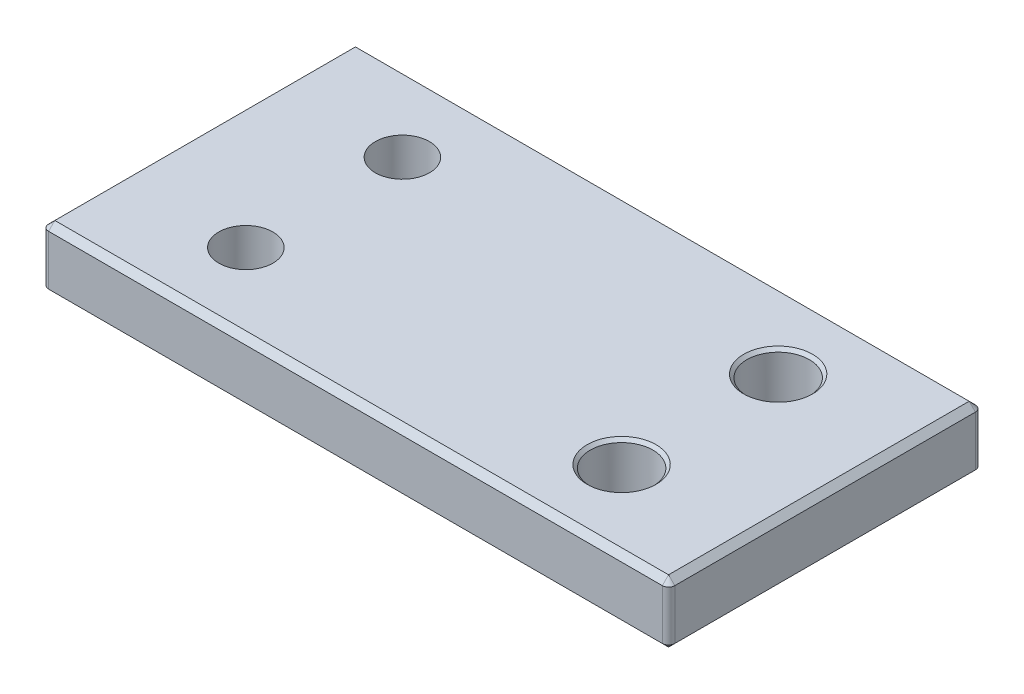
SolidWorks part; units mm, degrees
ref_plane "前基準面" through (0, 0, 0) normal (0, 0, 1) x (1, 0, 0)
ref_plane "上基準面" through (0, 0, 0) normal (0, 1, 0) x (1, 0, 0)
ref_plane "右基準面" through (0, 0, 0) normal (1, 0, 0) x (0, 0, -1)
ref_plane "平面1"
sketch "草圖1" plane through (0, 0, 0) normal (0, 1, 0) x (-1, 0, 0)
  line L0 (50, -25) -> (-50, -25)
  line L1 (-50, -25) -> (-50, 25)
  line L2 (-50, 25) -> (50, 25)
  line L3 (50, 25) -> (50, -25)
  dimension "D1" = 100
  dimension "D2" = 50
extrude "擠出1" add sketch "草圖1" along normal blind 10
sketch "草圖2" plane through (0, 10, 0) normal (0, 1, 0) x (-1, 0, 0)
  line L0 (50, -25) -> (50, 25) construction
  circle A0 centre (-30, -12.5) radius 5
  circle A1 centre (-30, 12.5) radius 5
  dimension "D1" = 10
  dimension "D2" = 10
  dimension "D3" = 25
  dimension "D4" = 32.5
  dimension "D5" = 80
extrude "擠出2" cut sketch "草圖2" against normal blind 10
hole_wizard "孔1" positions "草圖4" profile "草圖3" legacy
sketch "草圖4" plane through (0, 10, 0) normal (0, 1, 0) x (1, 0, 0)
  point P1 (-30, -12.5)
  point P2 (-30, 12.5)
sketch "草圖3" plane through (-30, 10, 12.5) normal (1, 0, 0) x (0, 0, 1)
  line L0 (0, 0) -> (0, 28.7978)
  line L1 (0, 28.7978) -> (4.3235, 26.2)
  line L2 (4.3235, 26.2) -> (4.3235, 0)
  line L4 (4.3235, 0) -> (0, 0)
  line L6 (0, 28.7978) -> (-4.3235, 26.2) construction
  line L7 (0, -4.2442) -> (0, 117.3081) construction
  dimension "直徑" = 8.647
  dimension "深度" = 26.2
  dimension "導頭角度" = 118
cosmetic thread "裝飾螺紋線1" parameters "D1"=10, "D2"=10.34
cosmetic thread "裝飾螺紋線2" parameters "D1"=10, "D2"=10.34
fillet "圓角3" radius 1 4 edges at (50, 5, -25) (50, 5, 25) (-50, 5, -25) (-50, 5, 25)
chamfer "倒角2" distance 1 distance2 1 16 edges at (0, 10, 25) (49.7071, 10, 24.7071) (50, 10, 0) (49.7071, 10, -24.7071) (0, 10, -25) (-49.7071, 10, -24.7071) (-50, 10, 0) (-49.7071, 10, 24.7071) (50, 0, 0) (49.7071, 0, 24.7071) (0, 0, 25) (-49.7071, 0, 24.7071) (-50, 0, 0) (-49.7071, 0, -24.7071) (0, 0, -25) (49.7071, 0, -24.7071)
chamfer "倒角3" distance 0.5 distance2 0.5 2 edges at (30, 10, 17.5) (30, 10, -7.5)
